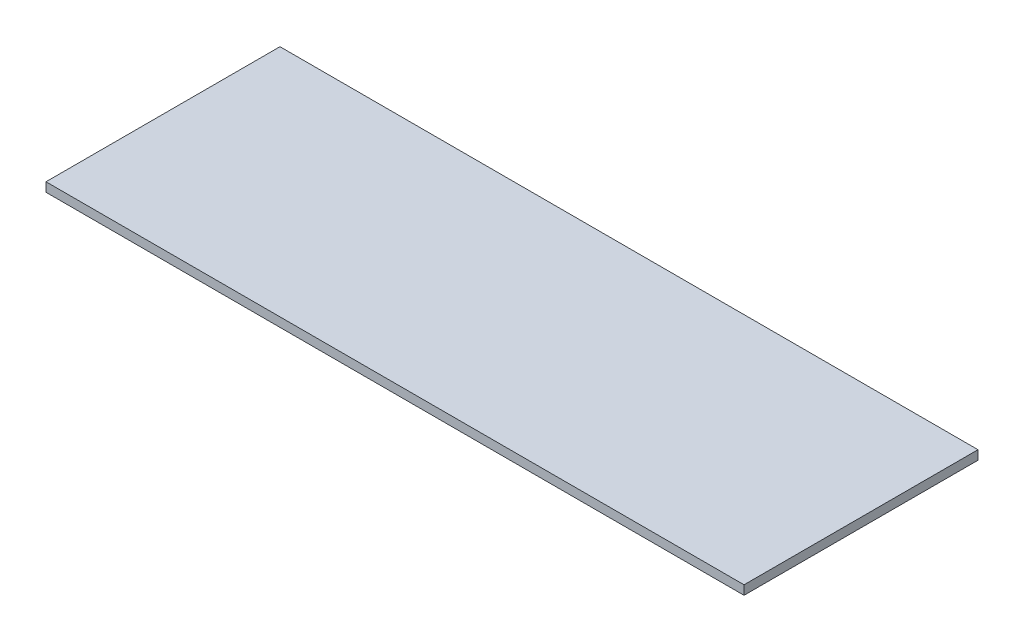
SolidWorks part; units mm, degrees
ref_plane "Front Plane" through (0, 0, 0) normal (0, 0, 1) x (1, 0, 0)
ref_plane "Top Plane" through (0, 0, 0) normal (0, 1, 0) x (1, 0, 0)
ref_plane "Right Plane" through (0, 0, 0) normal (1, 0, 0) x (0, 0, -1)
sketch "Sketch1" plane through (0, 0, 0) normal (0, 1, 0) x (1, 0, 0)
  line L1 (-59.1289, 93.5995) -> (304.8711, 93.5995)
  line L2 (-59.1289, 93.5995) -> (-59.1289, -28.4005)
  line L3 (-59.1289, -28.4005) -> (304.8711, -28.4005)
  line L4 (304.8711, 93.5995) -> (304.8711, -28.4005)
  dimension "D1" = 364
  dimension "D2" = 122
extrude "Boss-Extrude2" add sketch "Sketch1" along normal blind 4.7625
